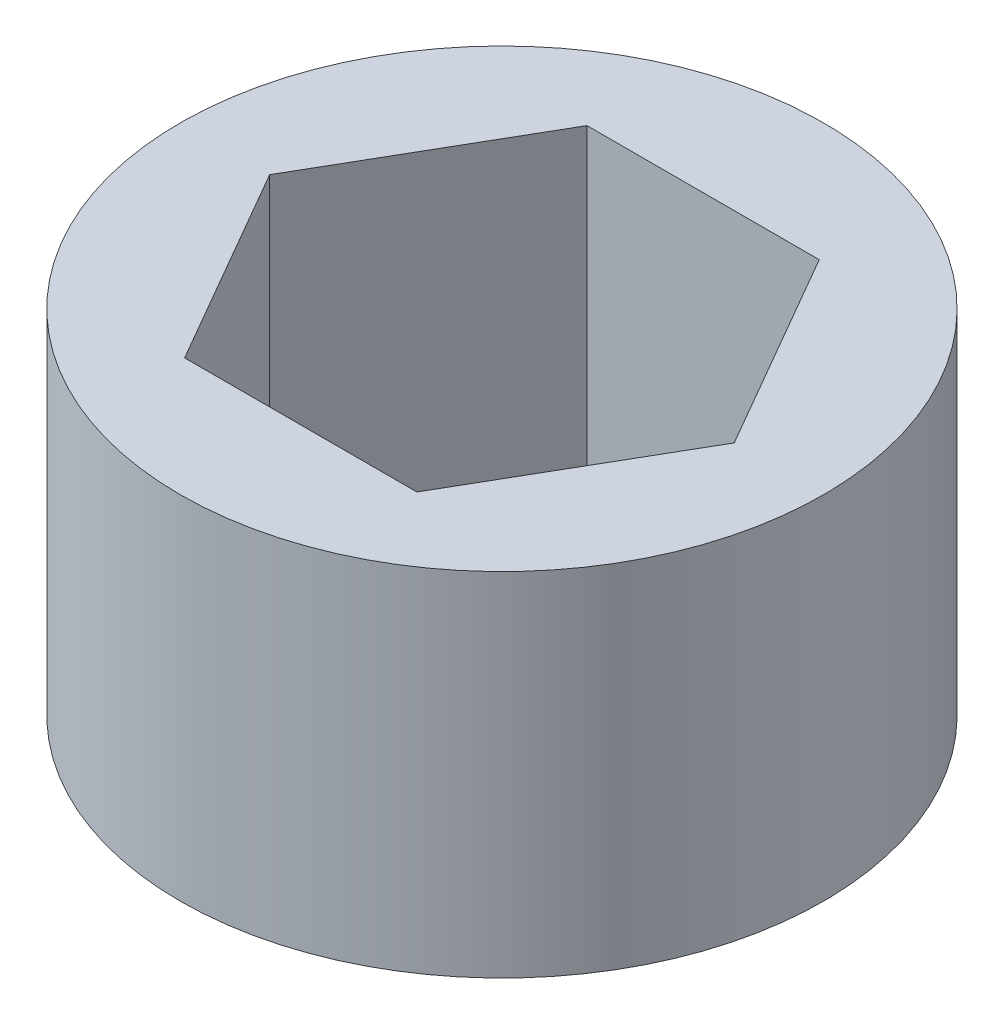
SolidWorks part; units mm, degrees
ref_plane "Front Plane" through (0, 0, 0) normal (0, 0, 1) x (1, 0, 0)
ref_plane "Top Plane" through (0, 0, 0) normal (0, 1, 0) x (1, 0, 0)
ref_plane "Right Plane" through (0, 0, 0) normal (1, 0, 0) x (0, 0, -1)
sketch "Sketch1" plane through (0, 0, 0) normal (0, 1, 0) x (1, 0, 0)
  line L1 (3.6662, -6.35) -> (7.3323, 0)
  line L2 (7.3323, 0) -> (3.6662, 6.35)
  line L3 (3.6662, 6.35) -> (-3.6662, 6.35)
  line L4 (-3.6662, 6.35) -> (-7.3323, 0)
  line L5 (-7.3323, 0) -> (-3.6662, -6.35)
  line L6 (-3.6662, -6.35) -> (3.6662, -6.35)
  circle A0 centre (0, 0) radius 6.35 construction
  circle A1 centre (0, 0) radius 10.16
  dimension "D1" = 12.7
  dimension "D2" = 20.32
extrude "Boss-Extrude1" add sketch "Sketch1" along normal blind 11.1125
